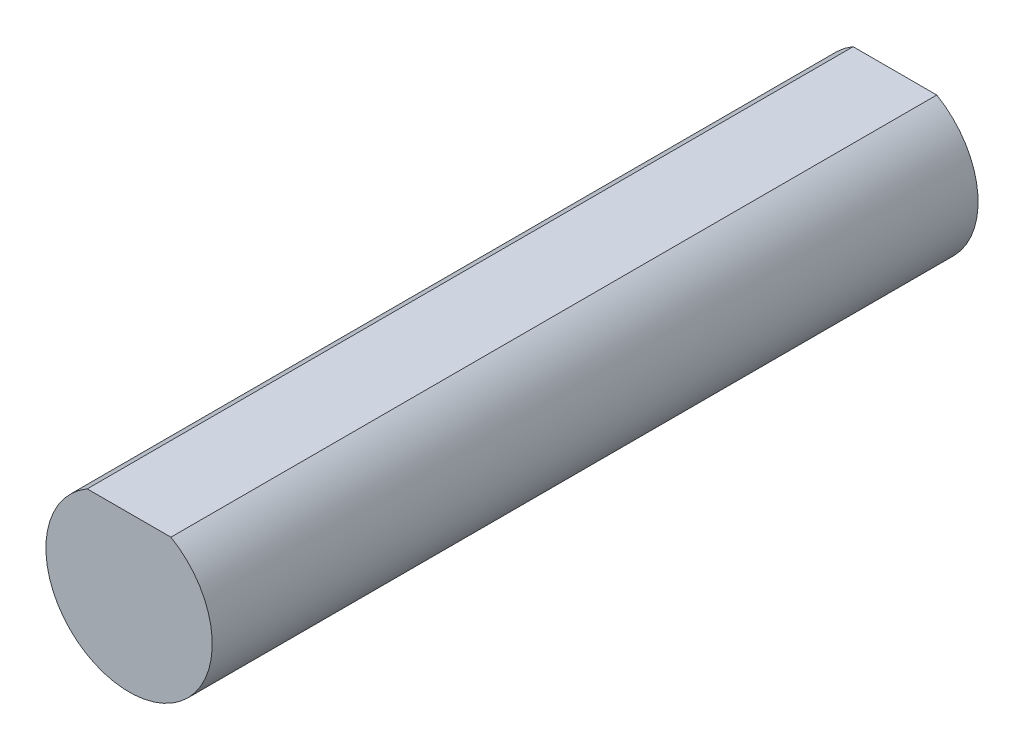
SolidWorks part; units mm, degrees
ref_plane "Front Plane" through (0, 0, 0) normal (0, 0, 1) x (1, 0, 0)
ref_plane "Top Plane" through (0, 0, 0) normal (0, 1, 0) x (1, 0, 0)
ref_plane "Right Plane" through (0, 0, 0) normal (1, 0, 0) x (0, 0, -1)
sketch "Sketch1" plane through (0, 0, 0) normal (0, 0, 1) x (1, 0, 0)
  line L1 (2, 3.4352) -> (-2, 3.4352)
  arc A1 (-2, 3.4352) -> (2, 3.4352) centre (0, 0) ccw
extrude "Boss-Extrude1" add sketch "Sketch1" along normal blind 36.6
